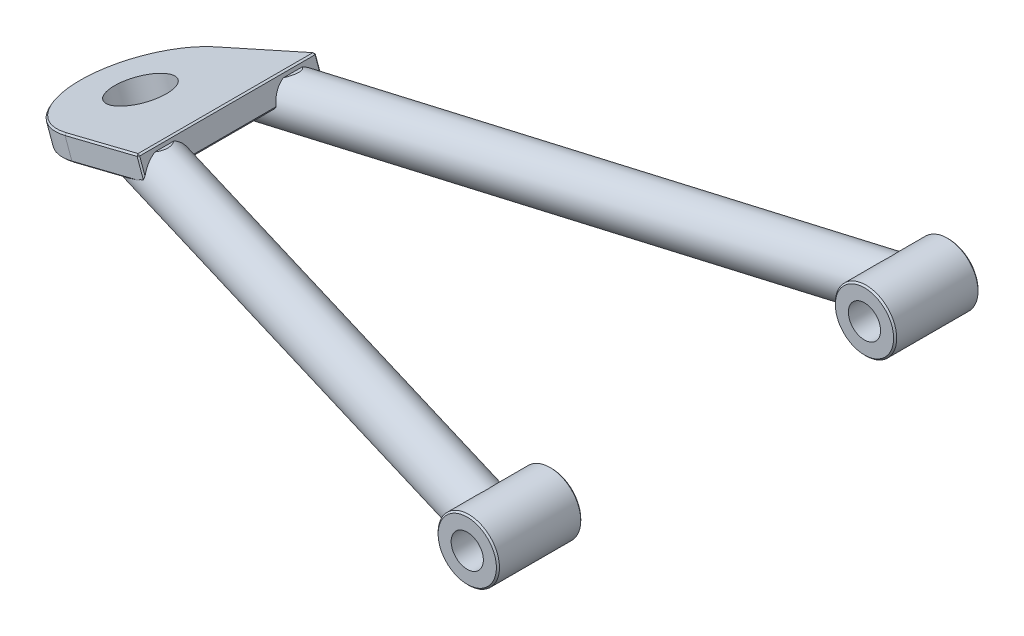
SolidWorks part; units mm, degrees
ref_plane "Front Plane" through (0, 0, 0) normal (0, 0, 1) x (1, 0, 0)
ref_plane "Top Plane" through (0, 0, 0) normal (0, 1, 0) x (1, 0, 0)
ref_plane "Right Plane" through (0, 0, 0) normal (1, 0, 0) x (0, 0, -1)
sketch "Sketch1" plane through (0, 0, 0) normal (0, 1, 0) x (1, 0, 0)
  line L0 (0, -178.98) -> (0, 178.98) construction
  line L1 (10.5, 101.98) -> (10.5, 169.3673) construction
  line L2 (0, 156.98) -> (-9.5, 156.98)
  line L3 (0, 156.98) -> (0, 101.98)
  line L4 (0, 101.98) -> (-9.5, 101.98)
  line L5 (-9.5, 156.98) -> (-9.5, 101.98)
  line L6 (0, 0) -> (-341.54, 0) construction
  line L11 (10.5, -101.98) -> (10.5, -169.3673) construction
  line L12 (0, -101.98) -> (-9.5, -101.98)
  line L13 (-9.5, -156.98) -> (-9.5, -101.98)
  line L14 (0, -156.98) -> (-9.5, -156.98)
  line L15 (0, -156.98) -> (0, -101.98)
  line L16 (-9.5, 129.48) -> (-341.54, 30) construction
  line L17 (-9.5, -129.48) -> (-341.54, -30) construction
  point P3 (0, 0)
  dimension "D1" = 357.96
  dimension "D2" = 22
  dimension "D3" = 9.5
  dimension "D4" = 55
  dimension "D5" = 20
  dimension "D6" = 341.54
  dimension "D7" = 30
revolve "Revolve1" add sketch "Sketch1" angle 360 about L1
ref_plane "Plane1" through (-341.54, 0, -30) normal (-0.9579, 0, 0.287) x (0.287, 0, 0.9579)
sketch "Sketch2" plane through (-341.54, 0, -30) normal (-0.9579, 0, 0.287) x (0.287, 0, 0.9579)
  circle A0 centre (0, 0) radius 15.5
  circle A1 centre (0, 0) radius 12.65
  dimension "D1" = 31
  dimension "D2" = 25.3
extrude "Boss-Extrude1" add sketch "Sketch2" along direction (-0.9579, 0, 0.287) on the side against the normal up to surface (341.9782 mm away)
ref_plane "Plane2" through (0, 0, 0) normal (0, 0, -1) x (-1, 0, 0)
ref_plane "Plane3" through (-341.54, 0, 30) normal (-0.9579, 0, -0.287) x (-0.287, 0, 0.9579)
sketch "Sketch3" plane through (-341.54, 0, 30) normal (-0.9579, 0, -0.287) x (-0.287, 0, 0.9579)
  circle A0 centre (0, 0) radius 15.5
  circle A1 centre (0, 0) radius 12.65
  dimension "D1" = 31
  dimension "D2" = 25.3
extrude "Boss-Extrude2" add sketch "Sketch3" along direction (-0.9579, 0, -0.287) on the side against the normal up to surface (351.2659 mm away)
sketch "Sketch10" plane through (-305.1602, 0, -91.4268) normal (-0.9579, 0, -0.287) x (-0.287, 0, 0.9579)
  circle A0 centre (126.7594, 0) radius 12.65 construction
  circle A1 centre (126.7594, 0) radius 12.65 construction
  point P6 (126.7594, -12.65)
sketch "Sketch12" plane through (-305.1602, 0, 91.4268) normal (-0.9579, 0, 0.287) x (0.287, 0, 0.9579)
  circle A0 centre (-126.7594, 0) radius 12.65 construction
  circle A1 centre (-126.7594, 0) radius 12.65 construction
  point P6 (-126.7594, -12.65)
ref_plane "Plane4" through (-35.887, 98.5986, 0) normal (-0.342, 0.9397, 0) x (0, 0, -1)
sketch "Sketch8" plane through (-35.887, 98.5986, 0) normal (-0.342, 0.9397, 0) x (0, 0, -1)
  line L0 (-30, 320.9426) -> (30, 320.9426) construction
  line L1 (0, 320.9426) -> (0, 453.9985) construction
  line L2 (-58.1255, 278.9426) -> (58.1255, 278.9426)
  line L3 (0, 0) -> (0, 320.9426) construction
  line L4 (-58.1255, 278.9426) -> (-49.4901, 338.9426)
  line L5 (58.1255, 278.9426) -> (49.4901, 338.9426)
  circle A0 centre (0, 338.9426) radius 18
  arc A1 (-49.4901, 338.9426) -> (49.4901, 338.9426) centre (0, 331.8198) cw
  point P11 (0, 278.9426)
  dimension "D1" = 36
  dimension "D5" = 50
  dimension "D2" = 81.81
  dimension "D3" = 60
  dimension "D4" = 60
ref_plane "Plane5" through (-301.5874, -109.7688, 0) normal (-0.9397, -0.342, 0) x (0, 0, 1)
sketch "Sketch9" plane through (-301.5874, -109.7688, 0) normal (-0.9397, -0.342, 0) x (0, 0, 1)
  line L1 (100, 116.8136) -> (-100, 116.8136)
  line L2 (100, 116.8136) -> (100, 150.0479)
  line L3 (100, 150.0479) -> (-100, 150.0479)
  line L4 (-100, 116.8136) -> (-100, 150.0479)
  point P5 (0, 116.8136)
  dimension "D1" = 200
  dimension "D2" = 33.2344
extrude "Cut-Extrude2" cut sketch "Sketch9" against normal mid plane 397
extrude "Boss-Extrude3" add sketch "Sketch8" along normal blind 15
chamfer "Chamfer1" distance 1 angle 45 4 edges at (30.5, 0, -156.98) (30.5, 0, -101.98) (30.5, 0, 101.98) (30.5, 0, 156.98)
chamfer "Chamfer2" distance 1 angle 45 10 edges at (-298.0073, 3.1946, 0) (-300.9149, 11.1833, -58.1255) (-300.9149, 11.1833, 58.1255) (-303.1376, 17.29, 0) (-331.3284, 7.0294, -53.8078) (-331.3284, 7.0294, 53.8078) (-399.8105, -17.8961, 0) (-329.9189, -8.4202, -53.2379) (-329.9189, -8.4202, 53.2379) (-394.6802, -31.9915, 0)
chamfer "Chamfer3" distance 1 angle 45 2 edges at (-341.0778, -15.4161, -28.4574) (-341.0778, -15.4161, 28.4574)
equation "\"Inner diameter tube\" = 25.3mm "
equation "\"D2@Sketch2\"=\"Inner diameter tube\""
equation "\"D2@Sketch3\"=\"Inner diameter tube\""
equation "\"BoltNominalDiameter\" = 10mm "
equation "\"BushingInnerDiameter\" = 10.1mm "
